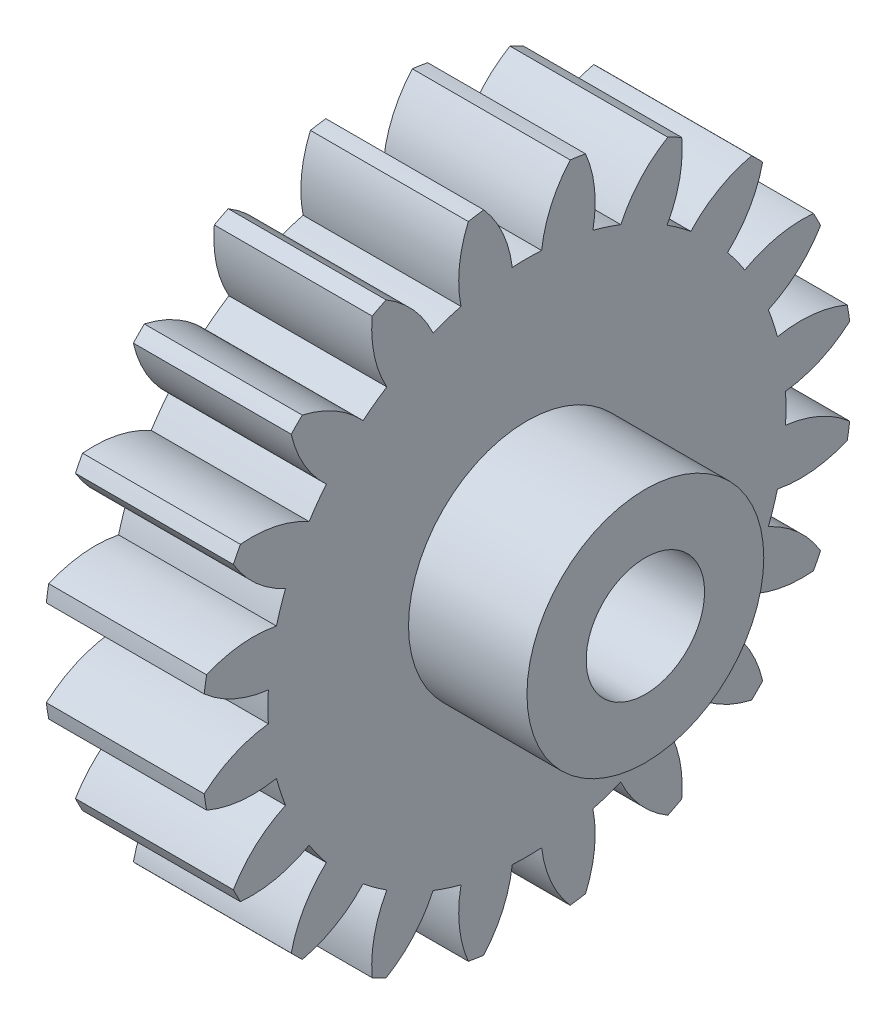
SolidWorks part; units mm, degrees
material "ABS PC"
ref_plane "Plane1" through (0, 0, 0) normal (0, 0, 1) x (1, 0, 0)
ref_plane "Plane2" through (0, 0, 0) normal (0, 1, 0) x (1, 0, 0)
ref_plane "Plane3" through (0, 0, 0) normal (1, 0, 0) x (0, 0, -1)
sketch "HoldingSke" plane through (0, 0, 0) normal (0, 1, 0) x (1, 0, 0)
  line L0 (0, 0) -> (0.6265, -0.228)
  line L1 (-15, 0) -> (100, 0) construction
  line L2 (0, 0) -> (-2.1039, 2.3779)
  line L3 (0, 0) -> (-11.863, 4.5341)
  line L4 (0, 0) -> (8.1152, 2.9537)
  line L5 (0, 0) -> (-46.8476, -17.4728)
  line L6 (0, 0) -> (-6.6317, -4.4744)
  line L7 (-2.1039, 2.3779) -> (8.6586, 51.2059)
  line L8 (-76.2, 54.61) -> (-75.2, 54.61)
  line L9 (-71.009, 38.7566) -> (-53.1078, 45.2721)
  line L10 (-76.2, 71.12) -> (104.1128, 71.12)
  line L11 (0, 0) -> (-8, 0)
  line L12 (-76.2, 101.6) -> (-76.147, 101.6)
  line L13 (24.9733, 27.94) -> (52.9518, 28.4284)
  line L14 (24.9733, 27.94) -> (24.9743, 27.94)
  line L15 (24.9733, 27.94) -> (100.4006, 29.5858)
  line L16 (-63.627, -1.5) -> (-12.827, -1.5)
  circle A0 centre (0, 0) radius 3
  circle A1 centre (0, 0) radius 13.124
  circle A2 centre (0, 0) radius 37.5
  circle A3 centre (0, 0) radius 3
  dimension "MHD" = 26.248
  dimension "Hub_dia" = 75
  dimension "Bore" = 6
  dimension "MBD" = 6
  dimension "Num_teeth" = 20
  dimension "Pitch" = 0.6667
  dimension "Overall_len" = 50
  dimension "Show_teeth" = 20
  dimension "Thickness" = 8
  dimension "OAL" = 50.0001
  dimension "T_dim" = 1
  dimension "Ap" = 20
  dimension "H" = 19.05
  dimension "Pitch_radius" = 180.3128
  dimension "Width" = 8
  dimension "Backlash" = 0.053
  dimension "Addendum_fac" = 1
  dimension "Dedendum_fac" = 1.25
  dimension "Clearance_fac" = 0.25
  dimension "Dedendum_add" = 0.001
  dimension "Module" = 1.5
sketch "BasProSke" plane through (0, 0, 0) normal (0, 1, 0) x (1, 0, 0)
  line L0 (-10, 0) -> (60, 0) construction
  line L1 (0, 0) -> (0, 16.5)
  line L2 (0, 0) -> (8, 0)
  line L3 (8, 0) -> (8, 16.5)
  line L4 (8, 16.5) -> (0, 16.5)
  dimension "Thickness" = 8
  dimension "Diameter" = 33
revolve "Base-Revolve" add sketch "BasProSke" angle 360 about L0
sketch "TooCutSke" plane through (0, 0, 0) normal (1, 0, 0) x (0, 0, -1)
  line L1 (0, 0) -> (0, 107) construction
  line L2 (0, 0) -> (-1.2696, 14.9462) construction
  line L3 (0, 0) -> (-4.6808, 29.5532) construction
  line L4 (-1.2696, 14.9462) -> (-2.3404, 14.7766) construction
  arc A0 (0.7438, 13.1029) -> (-0.7438, 13.1029) centre (0, 0) ccw
  arc A1 (2.21, 16.377) -> (-2.21, 16.377) centre (0, 0) ccw
  circle A2 centre (0, 0) radius 15 construction
  circle A3 centre (0, 0) radius 14.0954 construction
  arc A4 (-0.7438, 13.1029) -> (-2.21, 16.377) centre (-6.7025, 12.3999) ccw
  arc A5 (2.21, 16.377) -> (0.7438, 13.1029) centre (6.7025, 12.3999) ccw
  dimension "Root_dia" = 26.248
  dimension "Overcut_dia" = 33.0508
  dimension "Pitch_dia" = 30
  dimension "Base_dia" = 28.1908
  dimension "Flank_rad" = 6
  dimension "Half_ang" = 9
  dimension "Half_CT" = 1.0841
extrude "ToothCut" cut sketch "TooCutSke" along normal through all
fillet "Breaks" [suppressed] radius 0.03
fillet "RootFillets" [suppressed] radius 0.376
pattern_circular "TeethCuts" count 20 every 18 about axis through (-10, 0, 0) along (1, 0, 0) of "ToothCut", "RootFillets", "Breaks"
sketch "HubNeaOneSke" plane through (0, 0, 0) normal (-1, 0, 0) x (0, 0, 1)
  circle A0 centre (0, 0) radius 13.124
  dimension "Diameter" = 26.248
extrude "HubNearOne" [suppressed] add sketch "HubNeaOneSke" along normal blind 42.0001
sketch "HubNeaBotSke" plane through (0, 0, 0) normal (-1, 0, 0) x (0, 0, 1)
  circle A0 centre (0, 0) radius 13.124
  dimension "Diameter" = 26.248
extrude "HubNearBoth" [suppressed] add sketch "HubNeaBotSke" along normal blind 21
ref_plane "FarPln" through (8, 0, 0) normal (1, 0, 0) x (0, 0, -1)
sketch "HubFarSke" plane through (8, 0, 0) normal (1, 0, 0) x (0, 0, -1)
  circle A0 centre (0, 0) radius 13.124
  dimension "Diameter" = 26.248
extrude "HubFar" [suppressed] add sketch "HubFarSke" along normal blind 21
sketch "BorSke" plane through (0, 0, 0) normal (1, 0, 0) x (0, 0, -1)
  circle A0 centre (0, 0) radius 3
  dimension "Diameter" = 6
extrude "Bore" cut sketch "BorSke" along normal mid plane 100.0001
sketch "KeySke" plane through (0, 0, 0) normal (1, 0, 0) x (0, 0, -1)
  line L0 (-1, 0) -> (-1, 4)
  line L1 (-1, 4) -> (1, 4)
  line L2 (1, 4) -> (1, 0)
  line L3 (0, 0) -> (0, 34) construction
  line L4 (-1, 0) -> (1, 0)
  dimension "Offset" = 4
  dimension "Width" = 2
extrude "Keyway" [suppressed] cut sketch "KeySke" along normal mid plane 100.0001
pattern_circular "Keyway2" [suppressed] count 2 every 90 about axis through (-10, 0, 0) along (1, 0, 0)
sketch "Sketch1" plane through (8, 0, 0) normal (1, 0, 0) x (0, 0, -1)
  circle A0 centre (0, 0) radius 6
  dimension "D1" = 12
extrude "Boss-Extrude1" add sketch "Sketch1" along normal blind 6
sketch "Sketch2" plane through (14, 0, 0) normal (1, 0, 0) x (0, 0, -1)
  circle A0 centre (0, 0) radius 3
  dimension "D1" = 6
extrude "Cut-Extrude1" cut sketch "Sketch2" against normal blind 6
equation "' \"Module@HoldingSke\" = 6.35"
equation "' \"Num_teeth@HoldingSke\" = 12"
equation "' \"Ap@HoldingSke\" =  20"
equation "' \"Ap@HoldingSke\" = 20"
equation "' \"Width@HoldingSke\" = 0.5 * 25.4"
equation "' \"Hub_dia@HoldingSke\"= 1 * 25.4"
equation "' \"Hub_dia@HoldingSke\" = 1 * 25.4"
equation "' \"Overall_len@HoldingSke\" = 1.0 * 25.4"
equation "' \"Bore@HoldingSke\" = 0.75 * 25.4"
equation "' \"T_dim@HoldingSke\" = 0.1 * 25.4"
equation "' \"Width@KeySke\" = 0.25 * 25.4"
equation "' \"Show_teeth@HoldingSke\" = 13"
equation "' \"Backlash@HoldingSke\" = 0.009 * 25.4"
equation "' \"Addendum_fac@HoldingSke\" = 1.0"
equation "' \"Dedendum_fac@HoldingSke\" = 1.25"
equation "' \"Dedendum_add@HoldingSke\" = 0.00005 * 25.4"
equation "' \"Clearance_fac@HoldingSke\" = 0.25"
equation "\"Pitch@HoldingSke\" = 1 / \"Module@HoldingSke\""
equation "\"Overcut_dia@TooCutSke\" = (\"Num_teeth@HoldingSke\" + 2 * \"Addendum_fac@HoldingSke\") / \"Pitch@HoldingSke\" + 0.002 * 25.4"
equation "\"Pitch_dia@TooCutSke\" = \"Num_teeth@HoldingSke\" / \"Pitch@HoldingSke\""
equation "\"Base_dia@TooCutSke\" = \"Num_teeth@HoldingSke\" / \"Pitch@HoldingSke\" * cos((\"Ap@HoldingSke\"  * 3.14159265 / 180))"
equation "\"Root_dia@TooCutSke\" = (\"Num_teeth@HoldingSke\" + 2) / \"Pitch@HoldingSke\" - 2 * (\"Addendum_fac@HoldingSke\" + \"Dedendum_fac@HoldingSke\") / \"Pitch@HoldingSke\" - \"Dedendum_add@HoldingSke\" * 2"
equation "\"Half_ang@TooCutSke\" = 180 / \"Num_teeth@HoldingSke\""
equation "\"Half_CT@TooCutSke\" = \"Num_teeth@HoldingSke\" / \"Pitch@HoldingSke\" * sin((3.14159265 / 2 / \"Num_teeth@HoldingSke\")) / 2 - 7 * \"Backlash@HoldingSke\" / 4"
equation "\"Flank_rad@TooCutSke\" = \"Num_teeth@HoldingSke\" / \"Pitch@HoldingSke\" / 5"
equation "\"Radius@RootFillets\" = \"Clearance_fac@HoldingSke\" / \"Pitch@HoldingSke\" + \"Dedendum_add@HoldingSke\""
equation "\"Break_rad@Breaks\" = 0.02 / \"Pitch@HoldingSke\""
equation "\"Thickness@HoldingSke\" = \"Width@HoldingSke\""
equation "\"OAL@HoldingSke\" = \"Thickness@HoldingSke\""
equation "\"MHD@HoldingSke\" = (\"Num_teeth@HoldingSke\" + 2) / \"Pitch@HoldingSke\" - 2 * (\"Addendum_fac@HoldingSke\" + \"Dedendum_fac@HoldingSke\")  / \"Pitch@HoldingSke\" - \"Dedendum_add@HoldingSke\" * 2"
equation "\"MBD@HoldingSke\" = (\"Num_teeth@HoldingSke\" + 2) / \"Pitch@HoldingSke\" - 2 * (\"Addendum_fac@HoldingSke\" + \"Dedendum_fac@HoldingSke\")  / \"Pitch@HoldingSke\" - \"Dedendum_add@HoldingSke\" * 2 - 0.002 * 25.4"
equation "\"MHD@HoldingSke\" = ((sgn( \"MHD@HoldingSke\" - \"Hub_dia@HoldingSke\" )-1)*( \"MHD@HoldingSke\" - \"Hub_dia@HoldingSke\" ))/-2+ \"Hub_dia@HoldingSke\""
equation "\"MBD@HoldingSke\" = ((sgn( \"MBD@HoldingSke\" - \"Bore@HoldingSke\" )-1)*( \"MBD@HoldingSke\" - \"Bore@HoldingSke\" ))/-2+ \"Bore@HoldingSke\""
equation "\"OAL@HoldingSke\" = ((sgn( \"OAL@HoldingSke\" - \"Overall_len@HoldingSke\" )+1)*( \"OAL@HoldingSke\" - \"Overall_len@HoldingSke\" ))/2 + \"Overall_len@HoldingSke\" + 0.000002 * 25.4"
equation "\"Num_teeth@TeethCuts\" = int( \"Show_teeth@HoldingSke\" ) + 1"
equation "\"Num_teeth@TeethCuts\" = ((sgn( \"Num_teeth@TeethCuts\" - \"Num_teeth@HoldingSke\" )-1)*( \"Num_teeth@TeethCuts\" - \"Num_teeth@HoldingSke\" ))/-2+ \"Num_teeth@HoldingSke\""
equation "\"Num_teeth@TeethCuts\" = ((sgn( \"Num_teeth@TeethCuts\" - 2.0)+1)*( \"Num_teeth@TeethCuts\" - 2.0))/2 +2.0"
equation "\"Angle@TeethCuts\" = 360.0 / \"Num_teeth@HoldingSke\""
equation "\"Diameter@BasProSke\" = (\"Num_teeth@HoldingSke\" + 2 * \"Addendum_fac@HoldingSke\") / \"Pitch@HoldingSke\""
equation "\"Thickness@BasProSke\"  = \"Thickness@HoldingSke\""
equation "' \"Fillet_rad@BasProSke\" =  \"Thickness@HoldingSke\" * 0.05"
equation "' \"Fillet_rad@BasProSke\" = \"Thickness@HoldingSke\" * 0.05"
equation "\"MHD@HoldingSke\" = ((sgn( \"MHD@HoldingSke\" - \"Root_dia@TooCutSke\" )-1)*( \"MHD@HoldingSke\" - \"Root_dia@TooCutSke\" ))/-2+ \"Root_dia@TooCutSke\""
equation "\"Diameter@HubNeaOneSke\" = \"MHD@HoldingSke\""
equation "\"Length@HubNearOne\" = \"OAL@HoldingSke\" - \"Thickness@BasProSke\""
equation "\"Diameter@HubNeaBotSke\" = \"MHD@HoldingSke\""
equation "\"Length@HubNearBoth\" = ( \"OAL@HoldingSke\" - \"Thickness@BasProSke\" ) / 2.0"
equation "\"Thickness@FarPln\" = \"Thickness@BasProSke\""
equation "\"Diameter@HubFarSke\" = \"MHD@HoldingSke\""
equation "\"Length@HubFar\" = ( \"OAL@HoldingSke\" - \"Thickness@BasProSke\" ) / 2.0"
equation "\"Diameter@BorSke\" = \"MBD@HoldingSke\""
equation "\"D1@Bore\" = \"OAL@HoldingSke\" * 2.0"
equation "\"D1@Keyway\" = \"OAL@HoldingSke\" * 2.0"
equation "\"Offset@KeySke\" = \"T_dim@HoldingSke\" + \"MBD@HoldingSke\" / 2.0"
